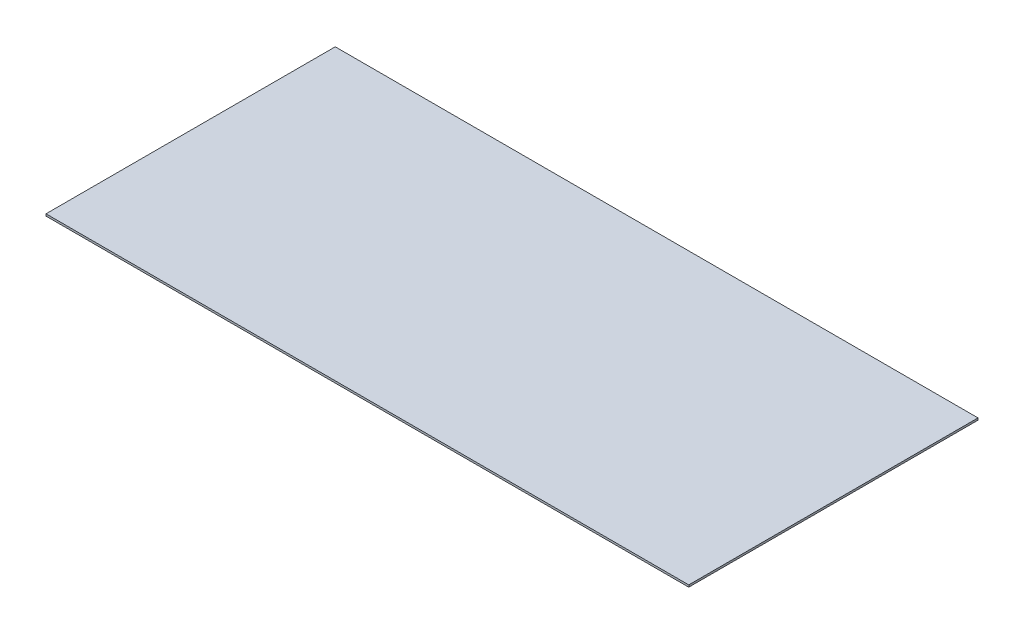
SolidWorks part; units mm, degrees
ref_plane "Front Plane" through (0, 0, 0) normal (0, 0, 1) x (1, 0, 0)
ref_plane "Top Plane" through (0, 0, 0) normal (0, 1, 0) x (1, 0, 0)
ref_plane "Right Plane" through (0, 0, 0) normal (1, 0, 0) x (0, 0, -1)
sketch "Sketch1" plane through (0, 0, 0) normal (0, 1, 0) x (1, 0, 0)
  line L1 (1016, -457.2) -> (-1016, -457.2)
  line L2 (1016, -457.2) -> (1016, 457.2)
  line L3 (1016, 457.2) -> (-1016, 457.2)
  line L4 (-1016, -457.2) -> (-1016, 457.2)
  line L5 (1016, -457.2) -> (-1016, 457.2) construction
  line L6 (1016, 457.2) -> (-1016, -457.2) construction
  point P0 (0, 0)
  dimension "D1" = 2032
  dimension "D2" = 914.4
extrude "Boss-Extrude1" add sketch "Sketch1" along normal blind 6.35
